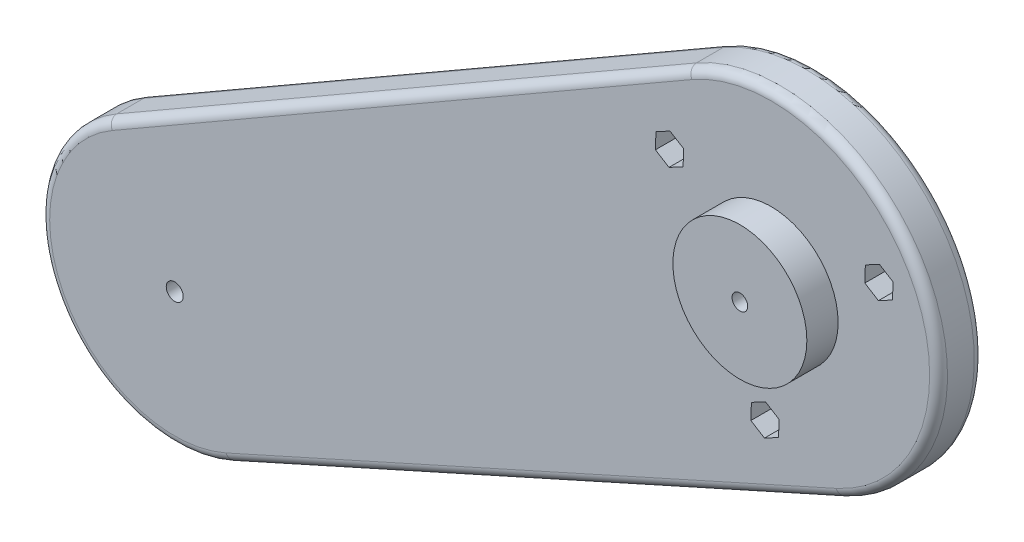
SolidWorks part; units mm, degrees
ref_plane "Front Plane" through (0, 0, 0) normal (0, 0, 1) x (1, 0, 0)
ref_plane "Top Plane" through (0, 0, 0) normal (0, 1, 0) x (1, 0, 0)
ref_plane "Right Plane" through (0, 0, 0) normal (1, 0, 0) x (0, 0, -1)
sketch "Sketch1" plane through (0, 0, 0) normal (0, 0, 1) x (1, 0, 0)
  line L3 (-148.5314, -42.2898) -> (-18.7193, 32.4937)
  line L4 (-121.2516, -95.6454) -> (15.3804, -34.2008)
  arc A0 (15.3804, -34.2008) -> (-18.7193, 32.4937) centre (0, 0) ccw
  arc A1 (-148.5314, -42.2898) -> (-121.2516, -95.6454) centre (-133.556, -68.2847) ccw
  dimension "D1" = 75
  dimension "D2" = 60
  dimension "D3" = 150
extrude "Boss-Extrude1" add sketch "Sketch1" along normal blind 10
sketch "Sketch3" plane through (0, 0, 10) normal (0, 0, 1) x (1, 0, 0)
  line L2 (-4.4241, -25.1889) -> (-4.5358, -28.7672)
  line L3 (27.2927, 14.0337) -> (24.2497, 15.9196)
  line L4 (24.2497, 15.9196) -> (21.095, 14.2272)
  line L5 (21.095, 14.2272) -> (20.9833, 10.6489)
  line L6 (20.9833, 10.6489) -> (24.0263, 8.7631)
  line L7 (24.0263, 8.7631) -> (27.181, 10.4555)
  line L8 (27.181, 10.4555) -> (27.2927, 14.0337)
  line L9 (-4.5358, -28.7672) -> (-1.4928, -30.6531)
  line L10 (-1.4928, -30.6531) -> (1.6619, -28.9607)
  line L11 (1.6619, -28.9607) -> (1.7736, -25.3824)
  line L12 (1.7736, -25.3824) -> (-1.2694, -23.4965)
  line L13 (-1.2694, -23.4965) -> (-4.4241, -25.1889)
  line L14 (-19.6022, 16.4259) -> (-22.6452, 18.3117)
  line L15 (-22.6452, 18.3117) -> (-25.7999, 16.6193)
  line L16 (-25.7999, 16.6193) -> (-25.9116, 13.0411)
  line L17 (-25.9116, 13.0411) -> (-22.8686, 11.1552)
  line L18 (-22.8686, 11.1552) -> (-19.7139, 12.8476)
  line L19 (-19.7139, 12.8476) -> (-19.6022, 16.4259)
  circle A1 centre (24.138, 12.3413) radius 3.1004 construction
  point P28 (0, 0)
  dimension "D2" = 3.58
  dimension "D3" = 3
fillet "Fillet1" radius 2 8 edges at (33.389, 17.0712, 10) (-52.9356, -64.9231, 10) (-160.2671, -81.9417, 10) (-83.6253, -4.8981, 10) (-52.9356, -64.9231, 0) (33.389, 17.0712, 0) (-83.6253, -4.8981, 0) (-160.2671, -81.9417, 0)
ref_plane "Plane1" through (0, 0, 5) normal (0, 0, 1) x (1, 0, 0)
extrude "Cut-Extrude8" cut sketch "Sketch3" against normal blind 5
sketch "Sketch10" plane through (0, 0, 5) normal (0, 0, 1) x (1, 0, 0)
  circle A1 centre (24.0401, 12.2913) radius 1.75
  dimension "D1" = 3.5
extrude "Cut-Extrude9" cut sketch "Sketch10" against normal blind 70 and the other way blind 1
pattern_circular "CirPattern1" count 3 over 360 about axis through (0, 0, 0) along (0, 0, 1) of "Cut-Extrude9"
sketch "Sketch12" plane through (0, 0, 10) normal (0, 0, 1) x (1, 0, 0)
  circle A5 centre (0, 0) radius 15
  dimension "D1" = 30
extrude "Boss-Extrude2" add sketch "Sketch12" along normal blind 7
sketch "Sketch14" plane through (0, 0, 0) normal (0, 0, -1) x (-1, 0, 0)
  line L0 (0, 0) -> (133.556, -68.2847)
  line L2 (137.136, -68.2847) -> (135.346, -65.1844)
  line L3 (135.346, -65.1844) -> (131.766, -65.1844)
  line L4 (131.766, -65.1844) -> (129.976, -68.2847)
  line L5 (129.976, -68.2847) -> (131.766, -71.3851)
  line L6 (131.766, -71.3851) -> (135.346, -71.3851)
  line L7 (135.346, -71.3851) -> (137.136, -68.2847)
  circle A0 centre (133.556, -68.2847) radius 3.1004 construction
  dimension "D1" = 3.58
extrude "Cut-Extrude11" cut sketch "Sketch14" against normal blind 5
sketch "Sketch15" plane through (0, 0, 5) normal (0, 0, -1) x (-1, 0, 0)
  circle A0 centre (133.556, -68.2847) radius 1.9
  dimension "D1" = 3.8
extrude "Cut-Extrude12" cut sketch "Sketch15" against normal blind 5
sketch "Sketch16" plane through (0, 0, 0) normal (0, 0, -1) x (-1, 0, 0)
  circle A0 centre (0, 0) radius 1.75
  dimension "D1" = 3.5
extrude "Cut-Extrude13" cut sketch "Sketch16" against normal blind 18
